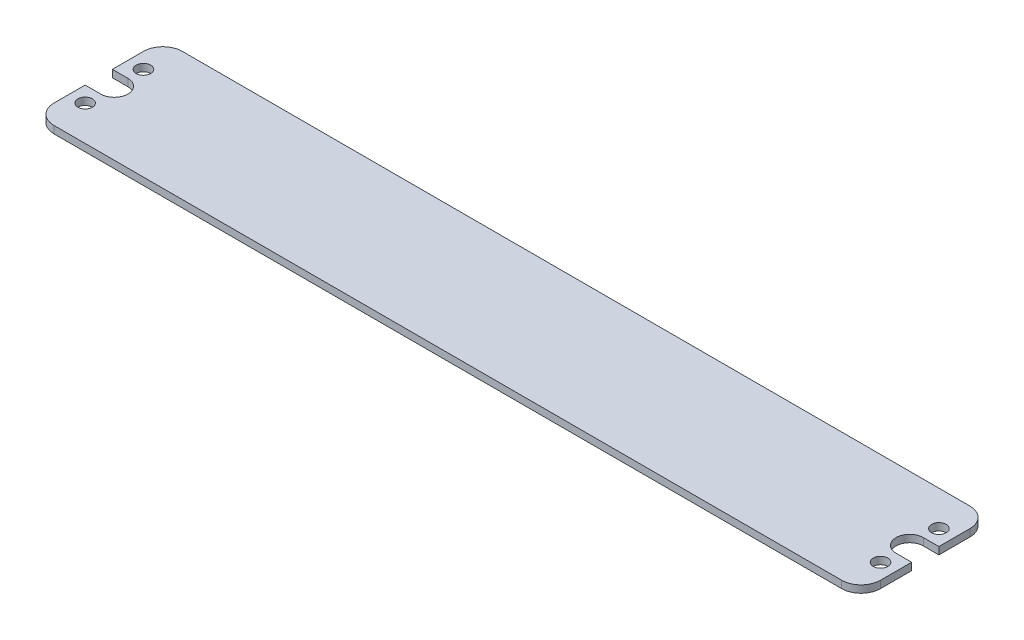
SolidWorks part; units mm, degrees
ref_plane "Front Plane" through (0, 0, 0) normal (0, 0, 1) x (1, 0, 0)
ref_plane "Top Plane" through (0, 0, 0) normal (0, 1, 0) x (1, 0, 0)
ref_plane "Right Plane" through (0, 0, 0) normal (1, 0, 0) x (0, 0, -1)
sketch "Sketch1" plane through (0, 0, 0) normal (0, 1, 0) x (1, 0, 0)
  line L0 (0, -41.91) -> (1.27, -41.91) construction
  line L1 (12.7, 0) -> (269.875, 0)
  line L2 (0, -12.7) -> (0, -33.02)
  line L3 (12.7, -83.82) -> (269.875, -83.82)
  line L4 (269.875, 0) -> (269.875, -83.82)
  line L5 (10.16, -50.8) -> (0, -50.8)
  line L6 (10.16, -33.02) -> (0, -33.02)
  line L7 (0, -50.8) -> (0, -71.12)
  line L8 (19.05, -41.91) -> (87.4324, -41.91) construction
  circle A0 centre (10.16, -60.96) radius 4.7625
  circle A1 centre (10.16, -22.86) radius 4.7625
  arc A2 (10.16, -50.8) -> (10.16, -33.02) centre (10.16, -41.91) ccw
  circle A3 centre (10.16, -22.86) radius 6.35 construction
  circle A4 centre (10.16, -60.96) radius 6.35 construction
  arc A5 (0, -71.12) -> (12.7, -83.82) centre (12.7, -71.12) ccw
  arc A6 (12.7, 0) -> (0, -12.7) centre (12.7, -12.7) ccw
  point P22 (0, -83.82)
  point P25 (0, 0)
  dimension "D3" = 9.525
  dimension "D4" = 9.525
  dimension "D5" = 17.78
  dimension "D10" = 41.91
  dimension "D11" = 12.7
  dimension "D12" = 12.7
  dimension "D13" = 12.7
  dimension "D1" = 83.82
  dimension "D2" = 269.875
  dimension "D6" = 19.05
  dimension "D7" = 19.05
  dimension "D8" = 10.16
  dimension "D9" = 10.16
extrude "Boss-Extrude1" add sketch "Sketch1" along normal blind 4.7625
mirror "Mirror1" about plane through (269.875, 4.7625, 0) normal (-1, 0, 0) of "Boss-Extrude1"
